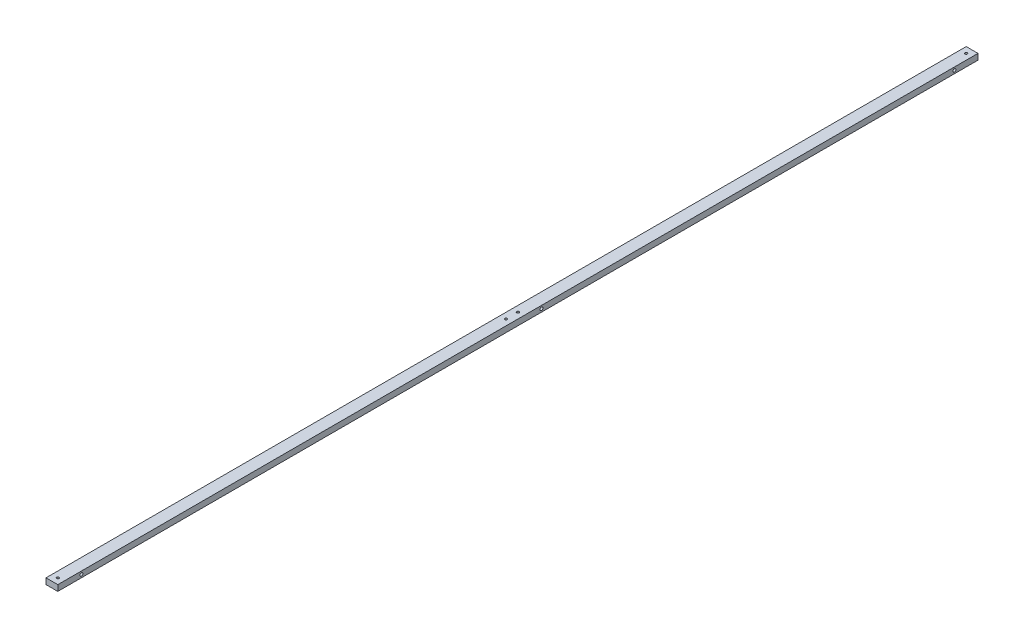
SolidWorks part; units mm, degrees
material "6061-T4 (SS)"
ref_plane "Front Plane" through (0, 0, 0) normal (0, 0, 1) x (1, 0, 0)
ref_plane "Top Plane" through (0, 0, 0) normal (0, 1, 0) x (1, 0, 0)
ref_plane "Right Plane" through (0, 0, 0) normal (1, 0, 0) x (0, 0, -1)
sketch "Sketch4" plane through (0, 0, 0) normal (0, 0, 1) x (1, 0, 0)
  line L1 (0, 0) -> (25.4, 0)
  line L2 (0, 0) -> (0, 12.7)
  line L3 (0, 12.7) -> (25.4, 12.7)
  line L4 (25.4, 0) -> (25.4, 12.7)
  dimension "D1" = 25.4
  dimension "D2" = 12.7
extrude "Boss-Extrude2" add sketch "Sketch4" along normal blind 1981.2
hole_wizard "1/4-20 Tapped Hole1" positions "Sketch5" profile "Sketch6" tap size "1/4-20" standard "ANSI Inch" end condition through all
sketch "Sketch5" plane through (0, 12.7, 0) normal (0, 1, 0) x (1, 0, 0)
  line L0 (25.4, -1981.2) -> (0, -1981.2) construction
  line L1 (0, -1981.2) -> (0, 0) construction
  point P0 (12.7, -1968.5)
  point P7 (12.7, -977.9)
  point P10 (12.7, -1003.3)
  point P13 (12.7, -12.7)
  dimension "D1" = 12.7
  dimension "D2" = 12.7
  dimension "D3" = 965.2
  dimension "D4" = 965.2
  dimension "D5" = 25.4
sketch "Sketch6" plane through (12.7, 12.7, 1968.5) normal (1, 0, 0) x (0, 0, 1)
  line L0 (0, 0) -> (0, 12.7)
  line L1 (0, 12.7) -> (2.5527, 12.7)
  line L2 (2.5527, 12.7) -> (2.5527, 0)
  line L5 (2.5527, 0) -> (0, 0)
  line L11 (0, -6.35) -> (0, 107.95) construction
  dimension "Thru Tap Drill Dia." = 5.1054
  dimension "Thru Tap Drill Depth" = 12.7
hole_wizard "1/4 (0.25) Diameter Hole1" positions "Sketch7" profile "Sketch9" hole size "1/4" standard "ANSI Inch" end condition through all
sketch "Sketch7" plane through (25.4, 0, 0) normal (1, 0, 0) x (0, 0, -1)
  line L0 (-1981.2, 0) -> (0, 0) construction
  line L1 (0, 0) -> (0, 12.7) construction
  line L2 (-1981.2, 0) -> (-1981.2, 12.7) construction
  point P0 (-50.8, 6.35)
  point P2 (-939.8, 6.35)
  point P4 (-1930.4, 6.35)
  dimension "D1" = 6.35
  dimension "D2" = 50.8
  dimension "D3" = 889
  dimension "D4" = 50.8
  dimension "D5" = 6.35
  dimension "D6" = 6.35
sketch "Sketch9" plane through (25.4, 6.35, 50.8) normal (0, 1, 0) x (0, 0, -1)
  line L0 (0, 0) -> (0, 25.4)
  line L1 (0, 25.4) -> (3.175, 25.4)
  line L2 (3.175, 25.4) -> (3.175, 0)
  line L5 (3.175, 0) -> (0, 0)
  line L11 (0, -6.35) -> (0, 107.95) construction
  dimension "Thru Hole Dia." = 6.35
  dimension "Thru Hole Depth" = 25.4
